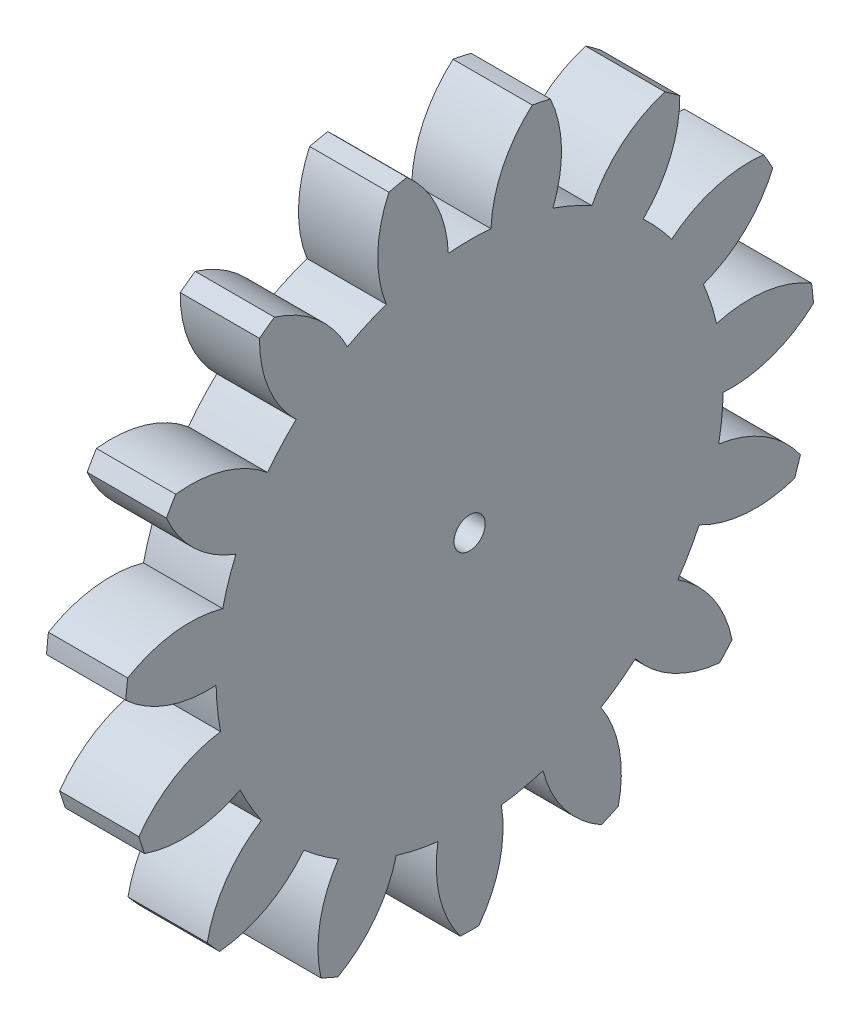
SolidWorks part; units mm, degrees
ref_plane "Plane1" through (0, 0, 0) normal (0, 0, 1) x (1, 0, 0)
ref_plane "Plane2" through (0, 0, 0) normal (0, 1, 0) x (1, 0, 0)
ref_plane "Plane3" through (0, 0, 0) normal (1, 0, 0) x (0, 0, -1)
sketch "HoldingSke" plane through (0, 0, 0) normal (0, 1, 0) x (1, 0, 0)
  line L0 (0, 0) -> (0.1486, -0.0398)
  line L1 (-15, 0) -> (100, 0) construction
  line L2 (0, 0) -> (-2.1039, 2.3779)
  line L3 (0, 0) -> (-11.863, 4.5341)
  line L4 (0, 0) -> (8.3417, 2.2352)
  line L5 (0, 0) -> (-46.8476, -17.4728)
  line L6 (0, 0) -> (-10.5278, -7.1032)
  line L7 (-2.1039, 2.3779) -> (8.6586, 51.2059)
  line L8 (-76.2, 54.61) -> (-75.3, 54.61)
  line L9 (-71.009, 38.7566) -> (-53.1078, 45.2721)
  line L10 (-76.2, 71.12) -> (104.1128, 71.12)
  line L11 (0, 0) -> (-12.7, 0)
  line L12 (-76.2, 101.6) -> (-75.981, 101.6)
  line L13 (24.9733, 27.94) -> (52.9518, 28.4284)
  line L14 (24.9733, 27.94) -> (24.9743, 27.94)
  line L15 (24.9733, 27.94) -> (100.4006, 29.5858)
  line L16 (-63.627, -6.5) -> (-12.827, -6.5)
  circle A0 centre (0, 0) radius 2.5
  circle A1 centre (0, 0) radius 37.5
  circle A2 centre (0, 0) radius 37.5
  circle A3 centre (0, 0) radius 2.5
  dimension "MHD" = 75
  dimension "Hub_dia" = 75
  dimension "Bore" = 5
  dimension "MBD" = 5
  dimension "Num_teeth" = 15
  dimension "Pitch" = 0.1538
  dimension "Overall_len" = 50
  dimension "Show_teeth" = 15
  dimension "Thickness" = 12.7
  dimension "OAL" = 50.0001
  dimension "T_dim" = 0.9
  dimension "Ap" = 20
  dimension "H" = 19.05
  dimension "Pitch_radius" = 180.3128
  dimension "Width" = 12.7
  dimension "Backlash" = 0.219
  dimension "Addendum_fac" = 1
  dimension "Dedendum_fac" = 1.25
  dimension "Clearance_fac" = 0.25
  dimension "Dedendum_add" = 0.001
  dimension "Module" = 6.5
sketch "BasProSke" plane through (0, 0, 0) normal (0, 1, 0) x (1, 0, 0)
  line L0 (-10, 0) -> (60, 0) construction
  line L1 (0, 0) -> (0, 55.25)
  line L2 (0, 0) -> (12.7, 0)
  line L3 (12.7, 0) -> (12.7, 55.25)
  line L4 (12.7, 55.25) -> (0, 55.25)
  dimension "Thickness" = 12.7
  dimension "Diameter" = 110.5
revolve "Base-Revolve" add sketch "BasProSke" angle 360 about L0
sketch "TooCutSke" plane through (0, 0, 0) normal (1, 0, 0) x (0, 0, -1)
  line L1 (0, 0) -> (0, 107) construction
  line L2 (0, 0) -> (-5.4787, 48.4412) construction
  line L3 (0, 0) -> (-20.1765, 94.9228) construction
  line L4 (-5.4787, 48.4412) -> (-10.0882, 47.4614) construction
  arc A0 (3.4146, 40.4802) -> (-3.4146, 40.4802) centre (0, 0) ccw
  arc A1 (10.058, 54.3526) -> (-10.058, 54.3526) centre (0, 0) ccw
  circle A2 centre (0, 0) radius 48.75 construction
  circle A3 centre (0, 0) radius 45.81 construction
  arc A4 (-3.4146, 40.4802) -> (-10.058, 54.3526) centre (-22.898, 39.6767) ccw
  arc A5 (10.058, 54.3526) -> (3.4146, 40.4802) centre (22.898, 39.6767) ccw
  dimension "Root_dia" = 81.248
  dimension "Overcut_dia" = 110.5508
  dimension "Pitch_dia" = 97.5
  dimension "Base_dia" = 91.62
  dimension "Flank_rad" = 19.5
  dimension "Half_ang" = 12
  dimension "Half_CT" = 4.7125
extrude "ToothCut" cut sketch "TooCutSke" along normal through all
fillet "Breaks" [suppressed] radius 0.13
fillet "RootFillets" [suppressed] radius 1.626
pattern_circular "TeethCuts" count 15 every 24 about axis through (-10, 0, 0) along (1, 0, 0) of "ToothCut", "RootFillets", "Breaks"
sketch "HubNeaOneSke" plane through (0, 0, 0) normal (-1, 0, 0) x (0, 0, 1)
  circle A0 centre (0, 0) radius 37.5
  dimension "Diameter" = 75
extrude "HubNearOne" [suppressed] add sketch "HubNeaOneSke" along normal blind 37.3001
sketch "HubNeaBotSke" plane through (0, 0, 0) normal (-1, 0, 0) x (0, 0, 1)
  circle A0 centre (0, 0) radius 37.5
  dimension "Diameter" = 75
extrude "HubNearBoth" [suppressed] add sketch "HubNeaBotSke" along normal blind 18.65
ref_plane "FarPln" through (12.7, 0, 0) normal (1, 0, 0) x (0, 0, -1)
sketch "HubFarSke" plane through (12.7, 0, 0) normal (1, 0, 0) x (0, 0, -1)
  circle A0 centre (0, 0) radius 37.5
  dimension "Diameter" = 75
extrude "HubFar" [suppressed] add sketch "HubFarSke" along normal blind 18.65
sketch "BorSke" plane through (0, 0, 0) normal (1, 0, 0) x (0, 0, -1)
  circle A0 centre (0, 0) radius 2.5
  dimension "Diameter" = 5
extrude "Bore" cut sketch "BorSke" along normal mid plane 100.0001
sketch "KeySke" plane through (0, 0, 0) normal (1, 0, 0) x (0, 0, -1)
  line L0 (-1, 0) -> (-1, 3.4)
  line L1 (-1, 3.4) -> (1, 3.4)
  line L2 (1, 3.4) -> (1, 0)
  line L3 (0, 0) -> (0, 34) construction
  line L4 (-1, 0) -> (1, 0)
  dimension "Offset" = 3.4
  dimension "Width" = 2
extrude "Keyway" [suppressed] cut sketch "KeySke" along normal mid plane 100.0001
pattern_circular "Keyway2" [suppressed] count 2 every 90 about axis through (-10, 0, 0) along (1, 0, 0)
sketch "Sketch1" plane through (12.7, 0, 0) normal (1, 0, 0) x (0, 0, -1)
  circle A0 centre (0, 0) radius 48.75
equation "' \"Module@HoldingSke\" = 6.35"
equation "' \"Num_teeth@HoldingSke\" = 12"
equation "' \"Ap@HoldingSke\" =  20"
equation "' \"Ap@HoldingSke\" = 20"
equation "' \"Width@HoldingSke\" = 0.5 * 25.4"
equation "' \"Hub_dia@HoldingSke\"= 1 * 25.4"
equation "' \"Hub_dia@HoldingSke\" = 1 * 25.4"
equation "' \"Overall_len@HoldingSke\" = 1.0 * 25.4"
equation "' \"Bore@HoldingSke\" = 0.75 * 25.4"
equation "' \"T_dim@HoldingSke\" = 0.1 * 25.4"
equation "' \"Width@KeySke\" = 0.25 * 25.4"
equation "' \"Show_teeth@HoldingSke\" = 13"
equation "' \"Backlash@HoldingSke\" = 0.009 * 25.4"
equation "' \"Addendum_fac@HoldingSke\" = 1.0"
equation "' \"Dedendum_fac@HoldingSke\" = 1.25"
equation "' \"Dedendum_add@HoldingSke\" = 0.00005 * 25.4"
equation "' \"Clearance_fac@HoldingSke\" = 0.25"
equation "\"Pitch@HoldingSke\" = 1 / \"Module@HoldingSke\""
equation "\"Overcut_dia@TooCutSke\" = (\"Num_teeth@HoldingSke\" + 2 * \"Addendum_fac@HoldingSke\") / \"Pitch@HoldingSke\" + 0.002 * 25.4"
equation "\"Pitch_dia@TooCutSke\" = \"Num_teeth@HoldingSke\" / \"Pitch@HoldingSke\""
equation "\"Base_dia@TooCutSke\" = \"Num_teeth@HoldingSke\" / \"Pitch@HoldingSke\" * cos((\"Ap@HoldingSke\"  * 3.14159265 / 180))"
equation "\"Root_dia@TooCutSke\" = (\"Num_teeth@HoldingSke\" + 2) / \"Pitch@HoldingSke\" - 2 * (\"Addendum_fac@HoldingSke\" + \"Dedendum_fac@HoldingSke\") / \"Pitch@HoldingSke\" - \"Dedendum_add@HoldingSke\" * 2"
equation "\"Half_ang@TooCutSke\" = 180 / \"Num_teeth@HoldingSke\""
equation "\"Half_CT@TooCutSke\" = \"Num_teeth@HoldingSke\" / \"Pitch@HoldingSke\" * sin((3.14159265 / 2 / \"Num_teeth@HoldingSke\")) / 2 - 7 * \"Backlash@HoldingSke\" / 4"
equation "\"Flank_rad@TooCutSke\" = \"Num_teeth@HoldingSke\" / \"Pitch@HoldingSke\" / 5"
equation "\"Radius@RootFillets\" = \"Clearance_fac@HoldingSke\" / \"Pitch@HoldingSke\" + \"Dedendum_add@HoldingSke\""
equation "\"Break_rad@Breaks\" = 0.02 / \"Pitch@HoldingSke\""
equation "\"Thickness@HoldingSke\" = \"Width@HoldingSke\""
equation "\"OAL@HoldingSke\" = \"Thickness@HoldingSke\""
equation "\"MHD@HoldingSke\" = (\"Num_teeth@HoldingSke\" + 2) / \"Pitch@HoldingSke\" - 2 * (\"Addendum_fac@HoldingSke\" + \"Dedendum_fac@HoldingSke\")  / \"Pitch@HoldingSke\" - \"Dedendum_add@HoldingSke\" * 2"
equation "\"MBD@HoldingSke\" = (\"Num_teeth@HoldingSke\" + 2) / \"Pitch@HoldingSke\" - 2 * (\"Addendum_fac@HoldingSke\" + \"Dedendum_fac@HoldingSke\")  / \"Pitch@HoldingSke\" - \"Dedendum_add@HoldingSke\" * 2 - 0.002 * 25.4"
equation "\"MHD@HoldingSke\" = ((sgn( \"MHD@HoldingSke\" - \"Hub_dia@HoldingSke\" )-1)*( \"MHD@HoldingSke\" - \"Hub_dia@HoldingSke\" ))/-2+ \"Hub_dia@HoldingSke\""
equation "\"MBD@HoldingSke\" = ((sgn( \"MBD@HoldingSke\" - \"Bore@HoldingSke\" )-1)*( \"MBD@HoldingSke\" - \"Bore@HoldingSke\" ))/-2+ \"Bore@HoldingSke\""
equation "\"OAL@HoldingSke\" = ((sgn( \"OAL@HoldingSke\" - \"Overall_len@HoldingSke\" )+1)*( \"OAL@HoldingSke\" - \"Overall_len@HoldingSke\" ))/2 + \"Overall_len@HoldingSke\" + 0.000002 * 25.4"
equation "\"Num_teeth@TeethCuts\" = int( \"Show_teeth@HoldingSke\" ) + 1"
equation "\"Num_teeth@TeethCuts\" = ((sgn( \"Num_teeth@TeethCuts\" - \"Num_teeth@HoldingSke\" )-1)*( \"Num_teeth@TeethCuts\" - \"Num_teeth@HoldingSke\" ))/-2+ \"Num_teeth@HoldingSke\""
equation "\"Num_teeth@TeethCuts\" = ((sgn( \"Num_teeth@TeethCuts\" - 2.0)+1)*( \"Num_teeth@TeethCuts\" - 2.0))/2 +2.0"
equation "\"Angle@TeethCuts\" = 360.0 / \"Num_teeth@HoldingSke\""
equation "\"Diameter@BasProSke\" = (\"Num_teeth@HoldingSke\" + 2 * \"Addendum_fac@HoldingSke\") / \"Pitch@HoldingSke\""
equation "\"Thickness@BasProSke\"  = \"Thickness@HoldingSke\""
equation "' \"Fillet_rad@BasProSke\" =  \"Thickness@HoldingSke\" * 0.05"
equation "' \"Fillet_rad@BasProSke\" = \"Thickness@HoldingSke\" * 0.05"
equation "\"MHD@HoldingSke\" = ((sgn( \"MHD@HoldingSke\" - \"Root_dia@TooCutSke\" )-1)*( \"MHD@HoldingSke\" - \"Root_dia@TooCutSke\" ))/-2+ \"Root_dia@TooCutSke\""
equation "\"Diameter@HubNeaOneSke\" = \"MHD@HoldingSke\""
equation "\"Length@HubNearOne\" = \"OAL@HoldingSke\" - \"Thickness@BasProSke\""
equation "\"Diameter@HubNeaBotSke\" = \"MHD@HoldingSke\""
equation "\"Length@HubNearBoth\" = ( \"OAL@HoldingSke\" - \"Thickness@BasProSke\" ) / 2.0"
equation "\"Thickness@FarPln\" = \"Thickness@BasProSke\""
equation "\"Diameter@HubFarSke\" = \"MHD@HoldingSke\""
equation "\"Length@HubFar\" = ( \"OAL@HoldingSke\" - \"Thickness@BasProSke\" ) / 2.0"
equation "\"Diameter@BorSke\" = \"MBD@HoldingSke\""
equation "\"D1@Bore\" = \"OAL@HoldingSke\" * 2.0"
equation "\"D1@Keyway\" = \"OAL@HoldingSke\" * 2.0"
equation "\"Offset@KeySke\" = \"T_dim@HoldingSke\" + \"MBD@HoldingSke\" / 2.0"
